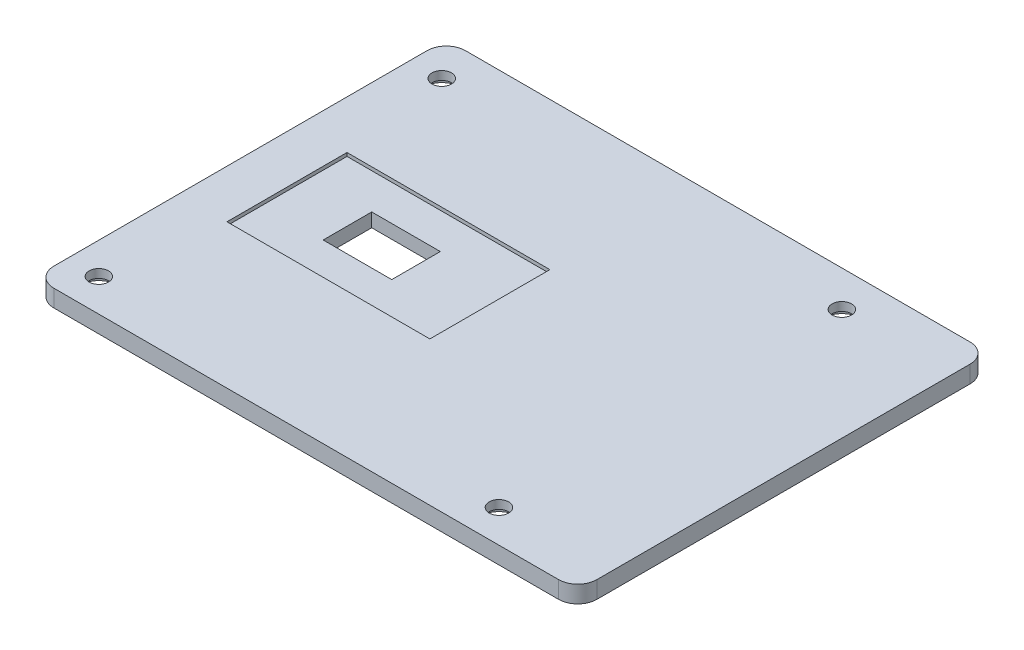
SolidWorks part; units mm, degrees
ref_plane "前视基准面" through (0, 0, 0) normal (0, 0, 1) x (1, 0, 0)
ref_plane "上视基准面" through (0, 0, 0) normal (0, 1, 0) x (1, 0, 0)
ref_plane "右视基准面" through (0, 0, 0) normal (1, 0, 0) x (0, 0, -1)
other "Configuration Table"
sketch "草图8" plane through (0, 0, 0) normal (0, 1, 0) x (1, 0, 0)
  line L1 (-21.65, 30) -> (66.65, 30)
  line L2 (-25, 26.65) -> (-25, -38.65)
  line L3 (-21.65, -42) -> (66.65, -42)
  line L4 (70, 26.65) -> (70, -38.65)
  arc A0 (-21.65, 30) -> (-25, 26.65) centre (-21.65, 26.65) ccw
  arc A1 (-25, -38.65) -> (-21.65, -42) centre (-21.65, -38.65) ccw
  arc A2 (66.65, 30) -> (70, 26.65) centre (66.65, 26.65) cw
  arc A3 (66.65, -42) -> (70, -38.65) centre (66.65, -38.65) ccw
  dimension "D5" = 3.35
  dimension "D6" = 3.35
  dimension "D7" = 3.35
  dimension "D8" = 3.35
  dimension "D1" = 25
  dimension "D2" = 70
  dimension "D3" = 30
  dimension "D4" = 42
extrude "凸台-拉伸2" add sketch "草图8" along normal blind 3
sketch "草图11" plane through (0, 3, 0) normal (0, 1, 0) x (1, 0, 0)
  circle A0 centre (-19.5, 23.71) radius 1.7
  circle A1 centre (-19.5, -36.29) radius 1.7
  circle A2 centre (50.5, 23.71) radius 1.7
  circle A3 centre (50.5, -36.29) radius 1.7
extrude "切除-拉伸2" cut sketch "草图11" against normal through all
sketch "草图13" plane through (0, 3, 0) normal (0, 1, 0) x (1, 0, 0)
  line L0 (-16.574, 4.205) -> (-16.574, -16.795)
  line L2 (-16.574, 4.205) -> (18.926, 4.205)
  line L3 (-16.574, -16.795) -> (18.926, -16.795)
  line L4 (18.926, 4.205) -> (18.926, -16.795)
  point P3 (-16.574, -6.295)
  dimension "D1" = 21
  dimension "D2" = 6.295
  dimension "D3" = 16.574
  dimension "D4" = 35.5
extrude "切除-拉伸3" cut sketch "草图13" against normal blind 0.6
sketch "草图14" plane through (0, 2.4, 0) normal (0, 1, 0) x (1, 0, 0)
  line L1 (-6, -2.04) -> (6, -2.04)
  line L2 (-6, -2.04) -> (-6, -10.54)
  line L3 (-6, -10.54) -> (6, -10.54)
  line L4 (6, -2.04) -> (6, -10.54)
  line L5 (-6, -2.04) -> (6, -10.54) construction
  line L6 (-6, -10.54) -> (6, -2.04) construction
  point P0 (0, -6.29)
  dimension "D1" = 12
  dimension "D2" = 8.5
  dimension "D3" = 6.29
  dimension "D4" = 0
extrude "切除-拉伸4" cut sketch "草图14" against normal through all
sketch "草图16" plane through (0, 0, 0) normal (0, -1, 0) x (1, 0, 0)
  circle A0 centre (-19.5, 36.29) radius 3.1
  circle A1 centre (-19.5, -23.71) radius 3.1
  circle A2 centre (50.5, 36.29) radius 3.1
  circle A3 centre (50.5, -23.71) radius 3.1
extrude "切除-拉伸5" cut sketch "草图16" against normal blind 1.5
sketch "草图17" plane through (0, 0, 0) normal (0, -1, 0) x (1, 0, 0)
  circle A0 centre (-19.5, 36.29) radius 3.35
  circle A1 centre (-19.5, -23.71) radius 3.35
  circle A2 centre (50.5, 36.29) radius 3.35
  circle A3 centre (50.5, -23.71) radius 3.35
extrude "切除-拉伸6" cut sketch "草图17" against normal blind 0.5
